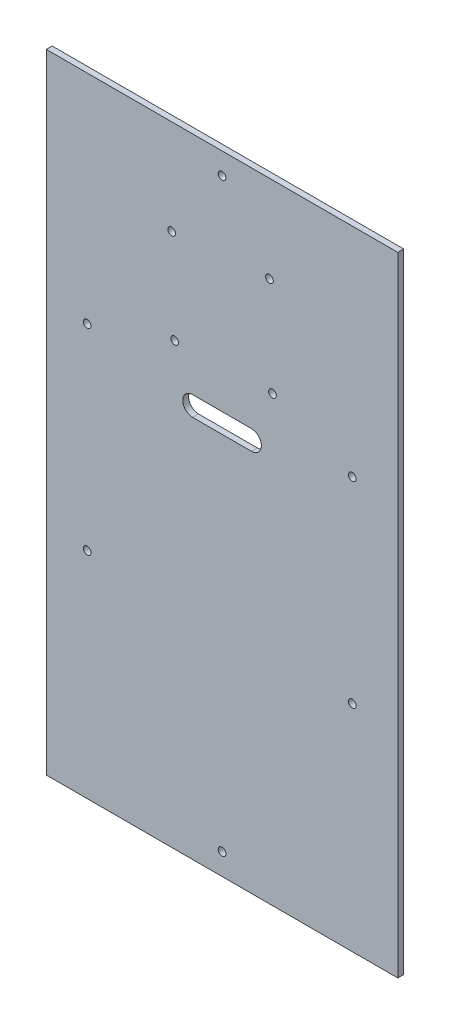
SolidWorks part; units mm, degrees
ref_plane "Alzado" through (0, 0, 0) normal (0, 0, 1) x (1, 0, 0)
ref_plane "Planta" through (0, 0, 0) normal (0, 1, 0) x (1, 0, 0)
ref_plane "Vista lateral" through (0, 0, 0) normal (1, 0, 0) x (0, 0, -1)
sketch "Croquis2" plane through (0, 0, 0) normal (0, 0, 1) x (1, 0, 0)
  line L1 (-89.5, 160) -> (89.5, 160)
  line L2 (-89.5, 160) -> (-89.5, -160)
  line L3 (-89.5, -160) -> (89.5, -160)
  line L4 (89.5, 160) -> (89.5, -160)
  dimension "D1" = 179
  dimension "D2" = 320
  dimension "D3" = 160
  dimension "D4" = 89.5
extrude "Saliente-Extruir1" add sketch "Croquis2" along normal blind 3
sketch "sup bores" plane through (0, 0, 3) normal (0, 0, 1) x (1, 0, 0)
  point P2 (0, 149)
  point P9 (0, -149)
  point P13 (66.31, -50.58)
  point P16 (-68.69, -50.58)
  point P18 (-68.69, 49.42)
  point P20 (66.31, 49.42)
hole_wizard "Taladro de margen para M3.51" positions "Croquis5" profile "Croquis6" hole size "M3.5" standard "Ansi Metric" end condition through all
sketch "Croquis5" plane through (0, 0, 3) normal (0, 0, 1) x (1, 0, 0)
  point P18 (0, 149)
  point P21 (-68.69, 49.42)
  point P24 (66.31, 49.42)
  point P27 (-68.69, -50.58)
  point P30 (0, -149)
  point P33 (66.31, -50.58)
sketch "Croquis6" plane through (0, 149, 3) normal (1, 0, 0) x (0, -1, 0)
  line L0 (0, 0) -> (0, 3)
  line L1 (0, 3) -> (1.95, 3)
  line L2 (1.95, 3) -> (1.95, 0)
  line L5 (1.95, 0) -> (0, 0)
  line L11 (0, -6.35) -> (0, 107.95) construction
  dimension "Diámetro de taladro hasta el siguiente" = 3.9
  dimension "Profundidad de taladro hasta el siguiente" = 3
sketch "robot arm bores" plane through (0, 0, 3) normal (0, 0, 1) x (1, 0, 0)
  line L0 (-15, 40) -> (15, 40) construction
  line L1 (-15, 45) -> (15, 45)
  line L2 (-15, 35) -> (15, 35)
  arc A0 (-15, 45) -> (-15, 35) centre (-15, 40) ccw
  arc A1 (15, 35) -> (15, 45) centre (15, 40) ccw
  point P1 (-24.1541, 64.318)
  point P3 (24.1492, 115.6701)
  point P5 (25.6736, 65.8424)
  point P10 (0, 40)
  point P18 (-25.6785, 114.1457)
  dimension "D1" = 40
  dimension "D2" = 30
  dimension "D3" = 10
extrude "Cortar-Extruir1" cut sketch "robot arm bores" against normal through all
hole_wizard "Taladro de margen para M3.52" positions "Croquis8" profile "Croquis9" hole size "M3.5" standard "Ansi Metric" end condition through all
sketch "Croquis8" plane through (0, 0, 3) normal (0, 0, 1) x (1, 0, 0)
  point P3 (-24.1541, 64.318)
  point P6 (25.6736, 65.8424)
  point P9 (24.1492, 115.6701)
  point P17 (-25.6234, 111.6658)
sketch "Croquis9" plane through (-24.1541, 64.318, 3) normal (1, 0, 0) x (0, -1, 0)
  line L0 (0, 0) -> (0, 3)
  line L1 (0, 3) -> (1.95, 3)
  line L2 (1.95, 3) -> (1.95, 0)
  line L5 (1.95, 0) -> (0, 0)
  line L11 (0, -6.35) -> (0, 107.95) construction
  dimension "Diámetro de taladro hasta el siguiente" = 3.9
  dimension "Profundidad de taladro hasta el siguiente" = 3
